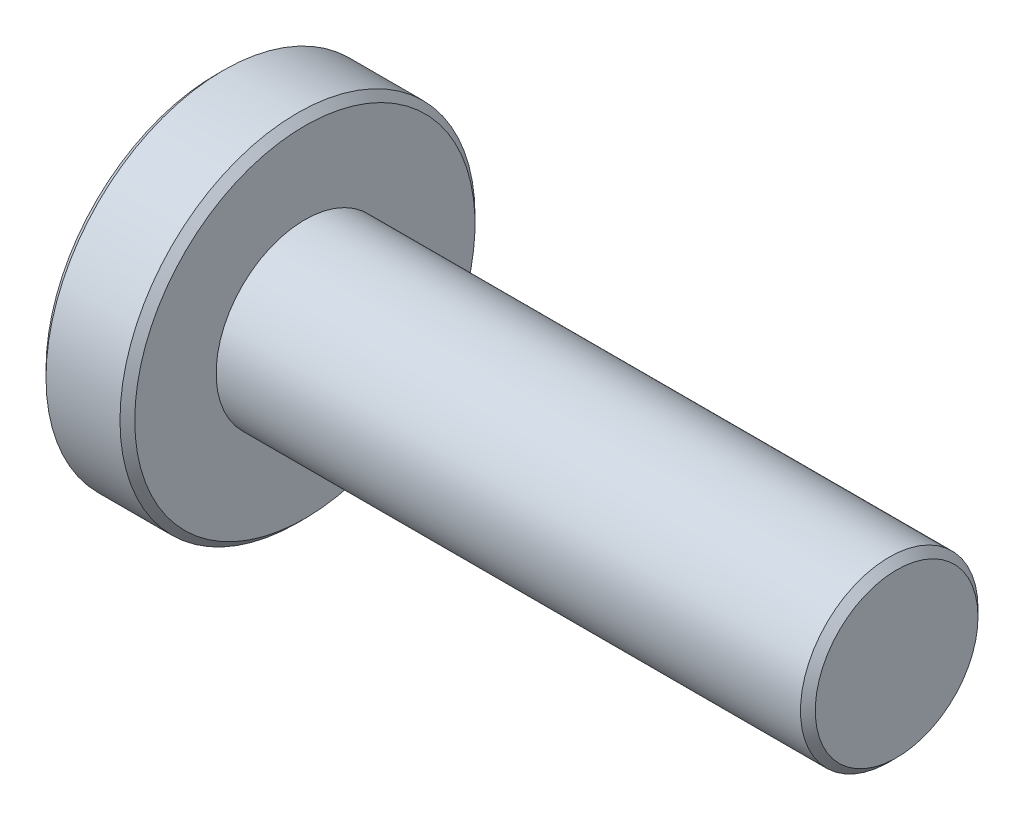
SolidWorks part; units mm, degrees
material "Nickel"
ref_plane "Front Plane" through (0, 0, 0) normal (0, 0, 1) x (1, 0, 0)
ref_plane "Top Plane" through (0, 0, 0) normal (0, 1, 0) x (1, 0, 0)
ref_plane "Right Plane" through (0, 0, 0) normal (1, 0, 0) x (0, 0, -1)
sketch "Sketch1" plane through (0, 0, 0) normal (1, 0, 0) x (0, 0, -1)
  circle A0 centre (0, 0) radius 3
  dimension "D1" = 6
extrude "SHAFT" add sketch "Sketch1" along normal blind 20
sketch "Sketch2" plane through (0, 0, 0) normal (-1, 0, 0) x (0, 0, 1)
  circle A0 centre (0, 0) radius 6
  dimension "D1" = 12
extrude "Boss-Extrude2" add sketch "Sketch2" along normal blind 3
chamfer "Chamfer1" distance 0.25 angle 45 3 edges at (-3, 0, 6) (0, 0, 6) (20, 0, -3)
